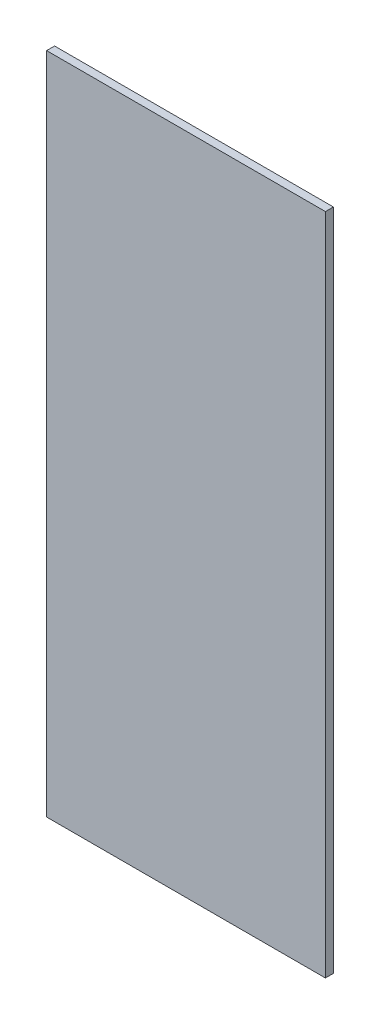
SolidWorks part; units mm, degrees
ref_plane "정면" through (0, 0, 0) normal (0, 0, 1) x (1, 0, 0)
ref_plane "윗면" through (0, 0, 0) normal (0, 1, 0) x (1, 0, 0)
ref_plane "우측면" through (0, 0, 0) normal (1, 0, 0) x (0, 0, -1)
sketch "스케치1" plane through (0, 0, 0) normal (0, 0, 1) x (1, 0, 0)
  line L1 (0, 0) -> (105, 0)
  line L2 (0, 0) -> (0, 250)
  line L3 (0, 250) -> (105, 250)
  line L4 (105, 0) -> (105, 250)
  dimension "D1" = 105
  dimension "D2" = 250
extrude "보스-돌출1" add sketch "스케치1" along normal blind 3
